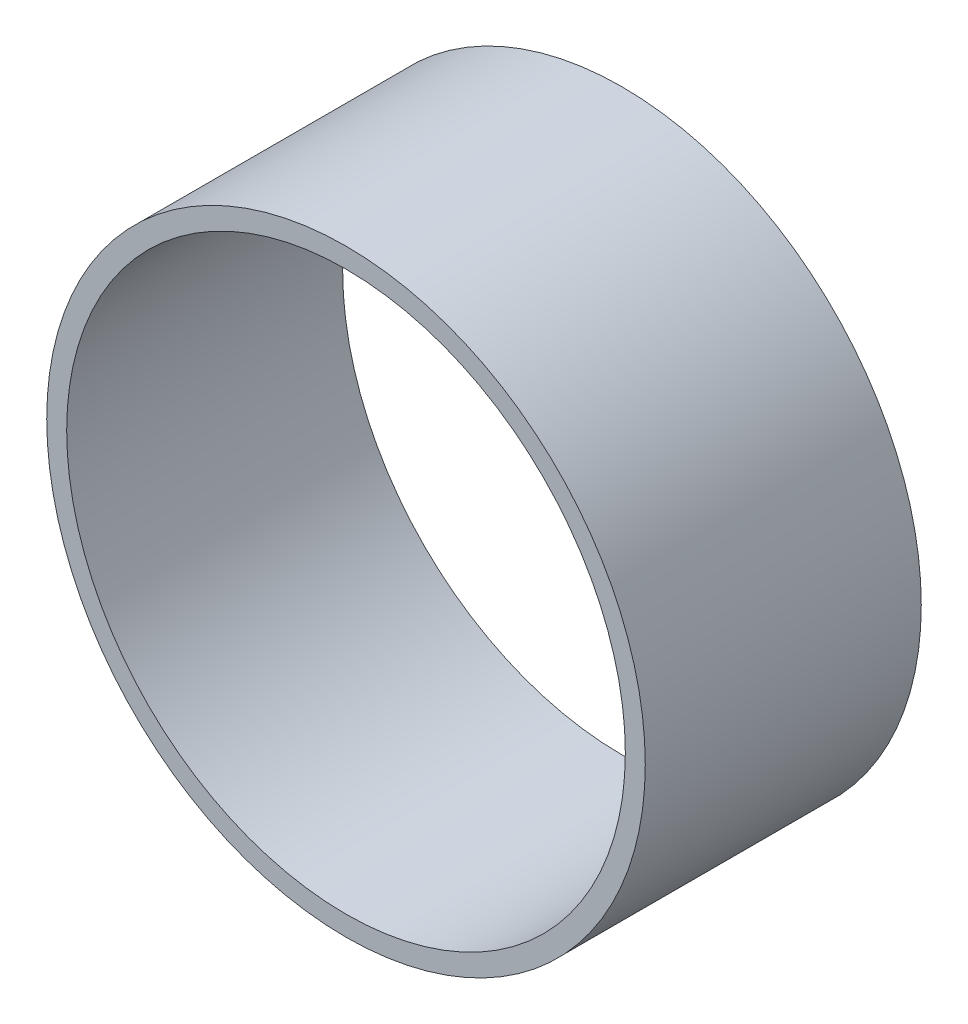
SolidWorks part; units mm, degrees
ref_plane "Front Plane" through (0, 0, 0) normal (0, 0, 1) x (1, 0, 0)
ref_plane "Top Plane" through (0, 0, 0) normal (0, 1, 0) x (1, 0, 0)
ref_plane "Right Plane" through (0, 0, 0) normal (1, 0, 0) x (0, 0, -1)
ref_plane "Plane1" through (0, 0, 30) normal (0, 0, 1) x (1, 0, 0)
sketch "Sketch1" plane through (0, 0, 30) normal (0, 0, 1) x (1, 0, 0)
  circle A0 centre (300, 300) radius 90
extrude "Boss-Extrude1" add sketch "Sketch1" along normal blind 83
sketch "Sketch2" plane through (0, 0, 113) normal (0, 0, 1) x (1, 0, 0)
  circle A0 centre (300, 300) radius 84
extrude "Cut-Extrude1" cut sketch "Sketch2" against normal blind 103
sketch "Sketch3" plane through (0, 0, 113) normal (0, 0, 1) x (1, 0, 0)
  circle A0 centre (387, 300) radius 3
sketch "Sketch4" plane through (0, 0, 113) normal (0, 0, 1) x (1, 0, 0)
  circle A0 centre (361.5183, 361.5183) radius 3
sketch "Sketch5" plane through (0, 0, 113) normal (0, 0, 1) x (1, 0, 0)
  circle A0 centre (300, 387) radius 3
sketch "Sketch6" plane through (0, 0, 113) normal (0, 0, 1) x (1, 0, 0)
  circle A0 centre (238.4817, 361.5183) radius 3
sketch "Sketch7" plane through (0, 0, 113) normal (0, 0, 1) x (1, 0, 0)
  circle A0 centre (213, 300) radius 3
sketch "Sketch8" plane through (0, 0, 113) normal (0, 0, 1) x (1, 0, 0)
  circle A0 centre (238.4817, 238.4817) radius 3
sketch "Sketch9" plane through (0, 0, 113) normal (0, 0, 1) x (1, 0, 0)
  circle A0 centre (300, 213) radius 3
sketch "Sketch10" plane through (0, 0, 113) normal (0, 0, 1) x (1, 0, 0)
  circle A0 centre (361.5183, 238.4817) radius 3
